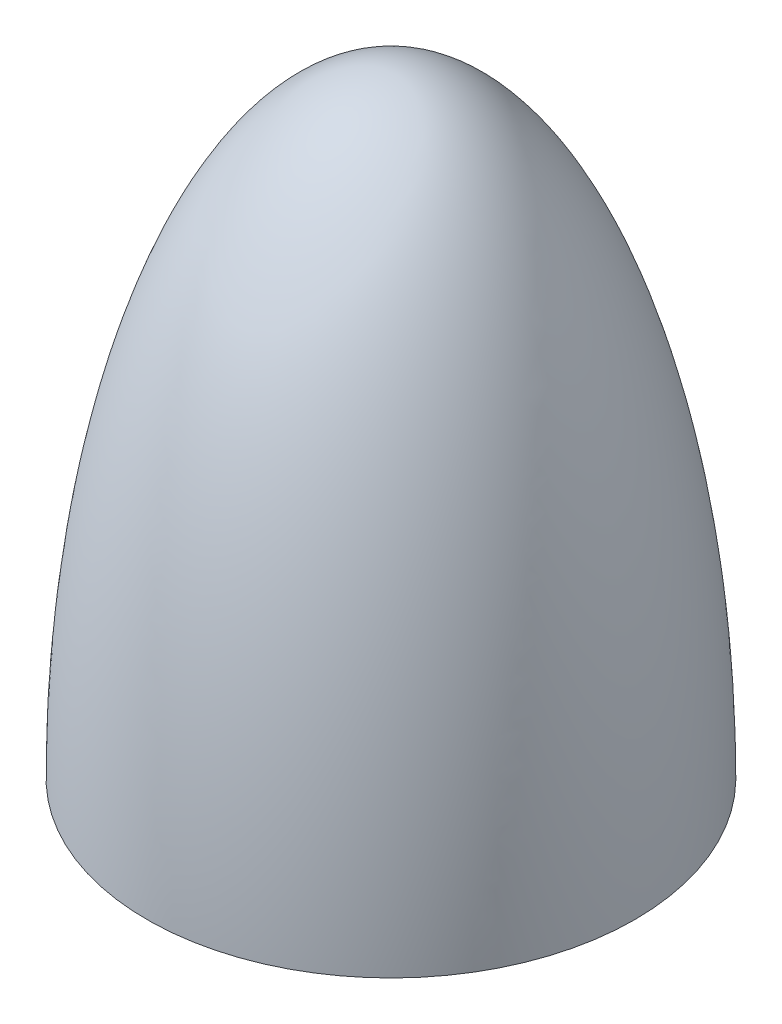
SolidWorks part; units mm, degrees
ref_plane "Front Plane" through (0, 0, 0) normal (0, 0, 1) x (1, 0, 0)
ref_plane "Top Plane" through (0, 0, 0) normal (0, 1, 0) x (1, 0, 0)
ref_plane "Right Plane" through (0, 0, 0) normal (1, 0, 0) x (0, 0, -1)
sketch "Sketch3" plane through (0, 0, 0) normal (0, 0, 1) x (1, 0, 0)
  line L0 (55.2, 0) -> (56.4, 0)
  line L1 (56.4, 0) -> (55.2, 0)
  line L2 (0, 0) -> (0, 141.2)
  ellipse E0 centre (0, 0) end of major axis (0, 140) minor radius 55.2 (55.2, 0) -> (0, 140) ccw
  spline S1 degree 3 poles (56.4, 0) (56.4, 18.3863) (53.5172, 55.1588) (43.24, 94.1761) (31.9105, 117.7567) (22.156, 130.9957) (11.4252, 139.2835) (3.8084, 141.2) (0, 141.2) knots 4.712389 4.712389 4.712389 4.712389 5.105088 5.497787 5.694137 5.890486 6.086836 6.283185 6.283185 6.283185 6.283185
revolve "Revolve3" add sketch "Sketch3" angle 360 about L2
